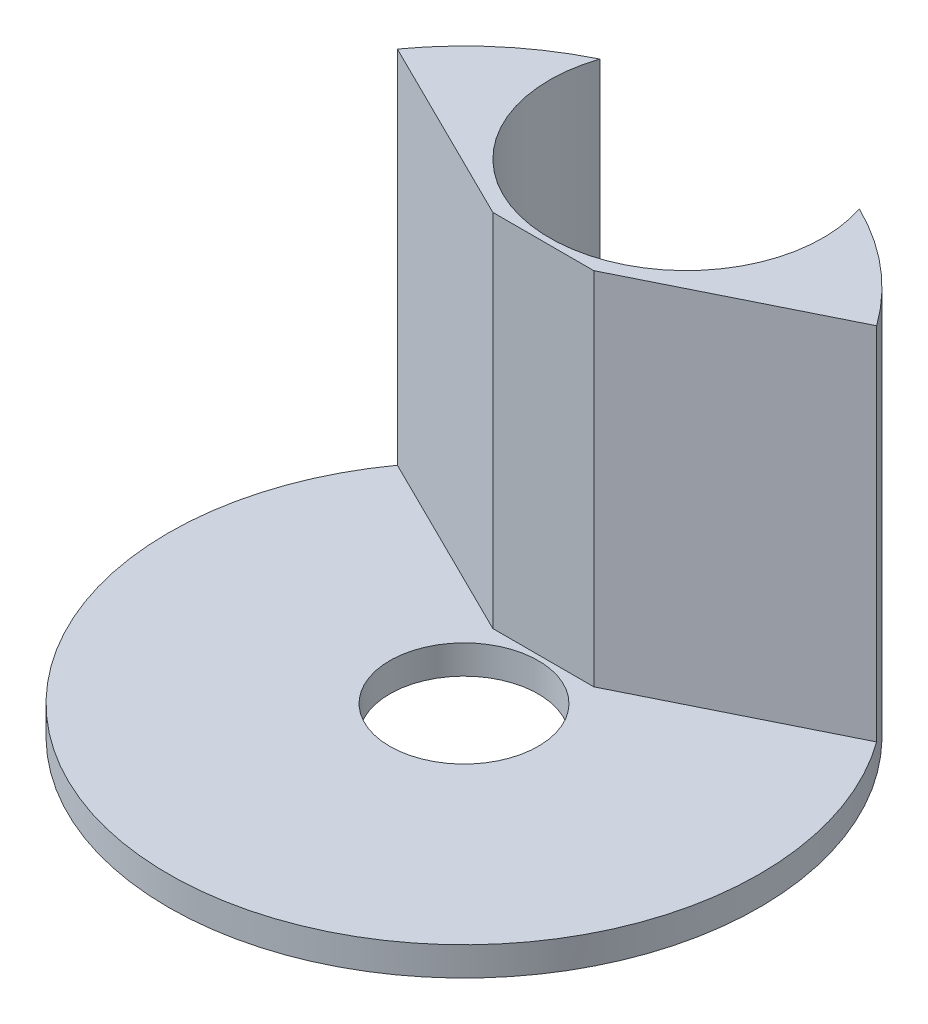
SolidWorks part; units mm, degrees
ref_plane "Front Plane" through (0, 0, 0) normal (0, 0, 1) x (1, 0, 0)
ref_plane "Top Plane" through (0, 0, 0) normal (0, 1, 0) x (1, 0, 0)
ref_plane "Right Plane" through (0, 0, 0) normal (1, 0, 0) x (0, 0, -1)
sketch "Sketch1" plane through (0, 0, 0) normal (0, 1, 0) x (1, 0, 0)
  circle A0 centre (0, 0) radius 20.5
  dimension "D1" = 41
extrude "Boss-Extrude1" add sketch "Sketch1" along normal blind 2
sketch "Sketch2" plane through (0, 2, 0) normal (0, 1, 0) x (1, 0, 0)
  circle A0 centre (0, 0) radius 5.15
  dimension "D1" = 10.3
extrude "Cut-Extrude1" cut sketch "Sketch2" against normal blind 3
sketch "Sketch3" plane through (0, 2, 0) normal (0, 1, 0) x (1, 0, 0)
  circle A0 centre (0, 13) radius 6.5
  dimension "D2" = 13
  dimension "D1" = 13
extrude "Cut-Extrude2" cut sketch "Sketch3" against normal blind 2
sketch "Sketch4" plane through (0, 2, 0) normal (0, 1, 0) x (1, 0, 0)
  line L0 (-3.5, 5.5) -> (-16.6208, 12)
  line L1 (3.5, 5.5) -> (16.6208, 12)
  line L4 (-3.5, 5.5) -> (3.5, 5.5)
  arc A0 (-16.6208, 12) -> (-9, 18.4187) centre (0, 0) cw
  circle A1 centre (0, 0) radius 20.5 construction
  arc A4 (9, 18.4187) -> (16.6208, 12) centre (0, 0) cw
  arc A6 (-9, 18.4187) -> (9, 18.4187) centre (0, 15.4184) ccw
  dimension "D1" = 12
  dimension "D2" = 12
  dimension "D3" = 5.5
  dimension "D4" = 5.5
  dimension "D5" = 3.5
  dimension "D6" = 3.5
  dimension "D7" = 9
  dimension "D8" = 9
extrude "Boss-Extrude4" add sketch "Sketch4" along normal blind 25
